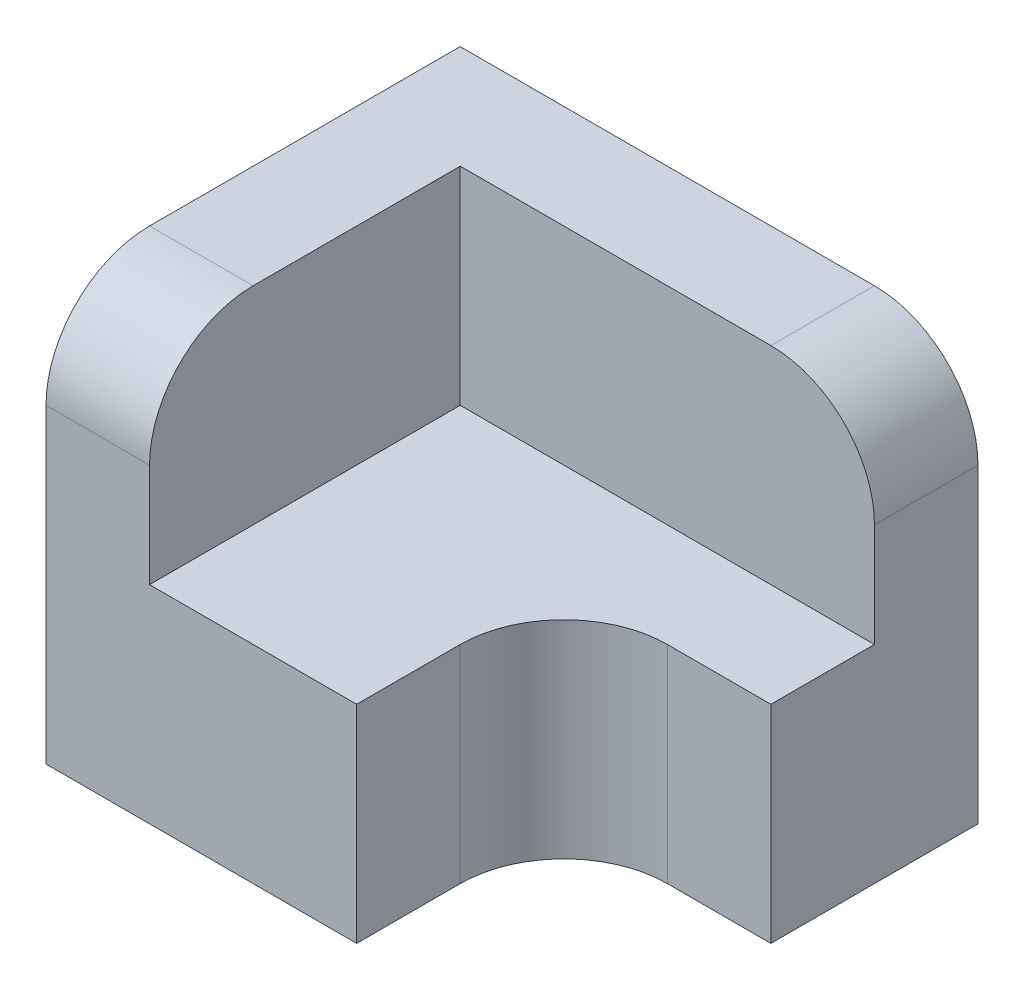
SolidWorks part; units mm, degrees
ref_plane "Front Plane" through (0, 0, 0) normal (0, 0, 1) x (1, 0, 0)
ref_plane "Top Plane" through (0, 0, 0) normal (0, 1, 0) x (1, 0, 0)
ref_plane "Right Plane" through (0, 0, 0) normal (1, 0, 0) x (0, 0, -1)
sketch "Sketch1" plane through (0, 0, 0) normal (0, 1, 0) x (1, 0, 0)
  line L0 (-45.6811, 29.9003) -> (-45.6811, -10.0997)
  line L1 (-45.6811, -10.0997) -> (-15.6811, -10.0997)
  line L2 (-15.6811, -10.0997) -> (-15.6811, -0.0997)
  line L3 (-5.6811, 9.9003) -> (4.3189, 9.9003)
  line L4 (4.3189, 9.9003) -> (4.3189, 29.9003)
  line L5 (4.3189, 29.9003) -> (-45.6811, 29.9003)
  arc A0 (-15.6811, -0.0997) -> (-5.6811, 9.9003) centre (-5.6811, -0.0997) cw
  dimension "D5" = 10
  dimension "D1" = 40
  dimension "D2" = 30
  dimension "D3" = 20
  dimension "D4" = 50
extrude "Boss-Extrude1" add sketch "Sketch1" along normal blind 20
sketch "Sketch2" plane through (-45.6811, 0, 0) normal (-1, 0, 0) x (0, 0, 1)
  line L0 (-29.9003, 20) -> (-29.9003, 40)
  line L1 (-29.9003, 40) -> (0.0997, 40)
  line L2 (10.0997, 30) -> (10.0997, 20)
  line L3 (10.0997, 20) -> (-29.9003, 20)
  arc A0 (10.0997, 30) -> (0.0997, 40) centre (0.0997, 30) ccw
  point P8 (10.0997, 40)
  dimension "D2" = 10
  dimension "D1" = 20
extrude "Boss-Extrude2" add sketch "Sketch2" against normal blind 10 contours L0 L1 A0 L2 L3
sketch "Sketch3" plane through (0, 0, -29.9003) normal (0, 0, -1) x (-1, 0, 0)
  line L0 (-4.3189, 20) -> (35.6811, 20)
  line L1 (35.6811, 20) -> (35.6811, 40)
  line L2 (35.6811, 40) -> (5.6811, 40)
  line L3 (-4.3189, 30) -> (-4.3189, 20)
  arc A0 (-4.3189, 30) -> (5.6811, 40) centre (5.6811, 30) cw
  dimension "D1" = 10
extrude "Boss-Extrude3" add sketch "Sketch3" against normal blind 10 contours L3 L0 L1 L2 A0
